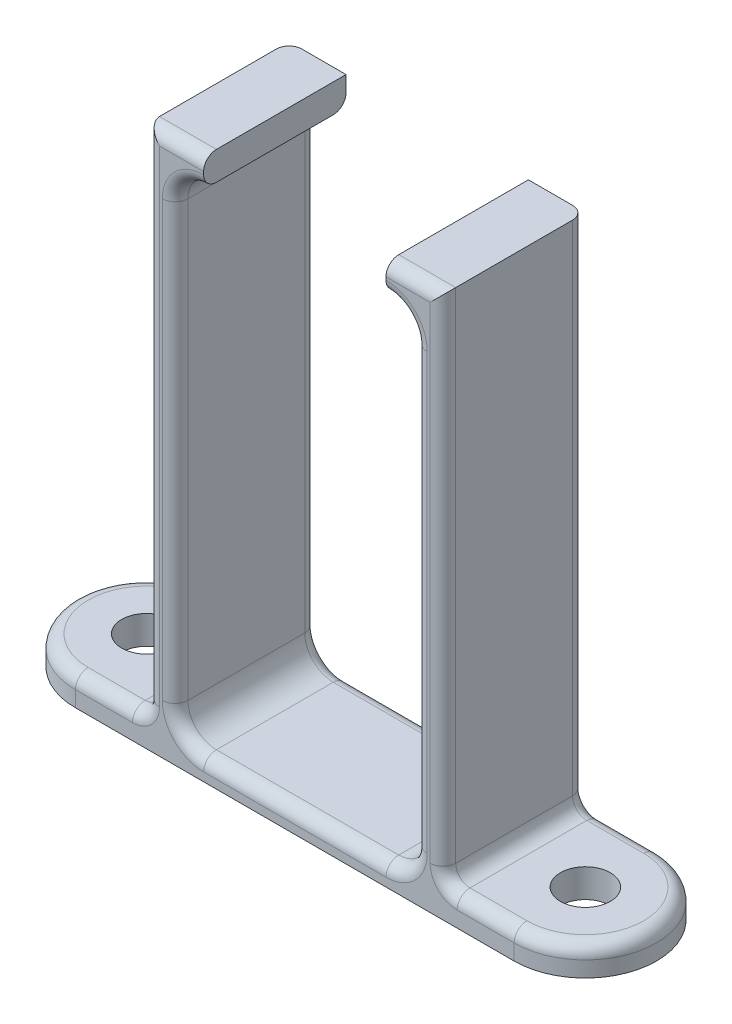
SolidWorks part; units mm, degrees
ref_plane "Alzado" through (0, 0, 0) normal (0, 0, 1) x (1, 0, 0)
ref_plane "Planta" through (0, 0, 0) normal (0, 1, 0) x (1, 0, 0)
ref_plane "Vista lateral" through (0, 0, 0) normal (1, 0, 0) x (0, 0, -1)
sketch "Croquis2" plane through (0, 0, 0) normal (0, 0, 1) x (1, 0, 0)
  line L0 (-10.4, 0) -> (10.4, 0)
  line L1 (10.4, 0) -> (10.4, 38)
  line L2 (10.4, 38) -> (6.4, 38)
  line L3 (6.4, 38) -> (6.4, 36)
  line L4 (8.4, 34) -> (8.4, 1.5)
  line L5 (8.4, 1.5) -> (-8.4, 1.5)
  line L6 (0, 1.5) -> (0, 0) construction
  line L7 (-6.4, 38) -> (-6.4, 36)
  line L8 (-10.4, 38) -> (-6.4, 38)
  line L9 (-8.4, 34) -> (-8.4, 1.5)
  line L10 (-10.4, 0) -> (-10.4, 38)
  arc A0 (6.4, 36) -> (8.4, 34) centre (6.4, 34) cw
  arc A1 (-6.4, 36) -> (-8.4, 34) centre (-6.4, 34) ccw
  dimension "D1" = 2
  dimension "D2" = 8.4
  dimension "D3" = 1.5
  dimension "D4" = 34.5
  dimension "D5" = 4
  dimension "D6" = 2
extrude "Saliente-Extruir1" add sketch "Croquis2" along normal blind 10
fillet "Redondeo1" radius 2 2 edges at (8.4, 1.5, 5) (-8.4, 1.5, 5)
sketch "Croquis4" plane through (0, 0, 0) normal (0, -1, 0) x (1, 0, 0)
  line L0 (-10.4, 0) -> (10.4, 0) construction
  line L1 (-10.4, 10) -> (-10.4, 0) construction
  line L2 (-10.4, 10) -> (-15.4, 10)
  line L3 (-10.4, 0) -> (-15.4, 0)
  line L4 (-10.4, 0) -> (-10.4, 10)
  line L5 (0, 0) -> (0, 12.3887) construction
  line L6 (10.4, 0) -> (15.4, 0)
  line L7 (10.4, 10) -> (15.4, 10)
  line L8 (10.4, 0) -> (10.4, 10)
  circle A0 centre (-15.4, 5) radius 3 construction
  arc A1 (-15.4, 10) -> (-15.4, 0) centre (-15.4, 5) ccw
  circle A2 centre (-15.4, 5) radius 1.75
  arc A3 (15.4, 10) -> (15.4, 0) centre (15.4, 5) cw
  circle A4 centre (15.4, 5) radius 3 construction
  circle A5 centre (15.4, 5) radius 1.75
  dimension "D1" = 6
  dimension "D4" = 10
  dimension "D5" = 3.5
  dimension "D2" = 5
  dimension "D3" = 5
extrude "Saliente-Extruir2" add sketch "Croquis4" against normal blind 2
fillet "Redondeo3" radius 1 2 edges at (10.4, 2, 5) (-10.4, 2, 5)
fillet "Redondeo4" radius 0.9 30 edges at (7.8142, 35.4142, 0) (7.8142, 35.4142, 10) (-7.8142, 35.4142, 0) (-7.8142, 35.4142, 10) (-8.4, 18.75, 10) (-8.4, 18.75, 0) (-7.8142, 2.0858, 10) (-7.8142, 2.0858, 0) (0, 1.5, 10) (0, 1.5, 0) (7.8142, 2.0858, 10) (7.8142, 2.0858, 0) (10.4, 20.5, 10) (10.4, 20.5, 0) (10.6929, 2.2929, 10) (10.6929, 2.2929, 0) (13.4, 2, 0) (20.4, 2, 5) (13.4, 2, 10) (-10.4, 20.5, 0) (-10.4, 20.5, 10) (-10.6929, 2.2929, 0) (-10.6929, 2.2929, 10) (-13.4, 2, 0) (-20.4, 2, 5) (-13.4, 2, 10) (8.4, 18.75, 0) (8.4, 18.75, 10) (8.4, 38, 10) (-8.4, 38, 10)
